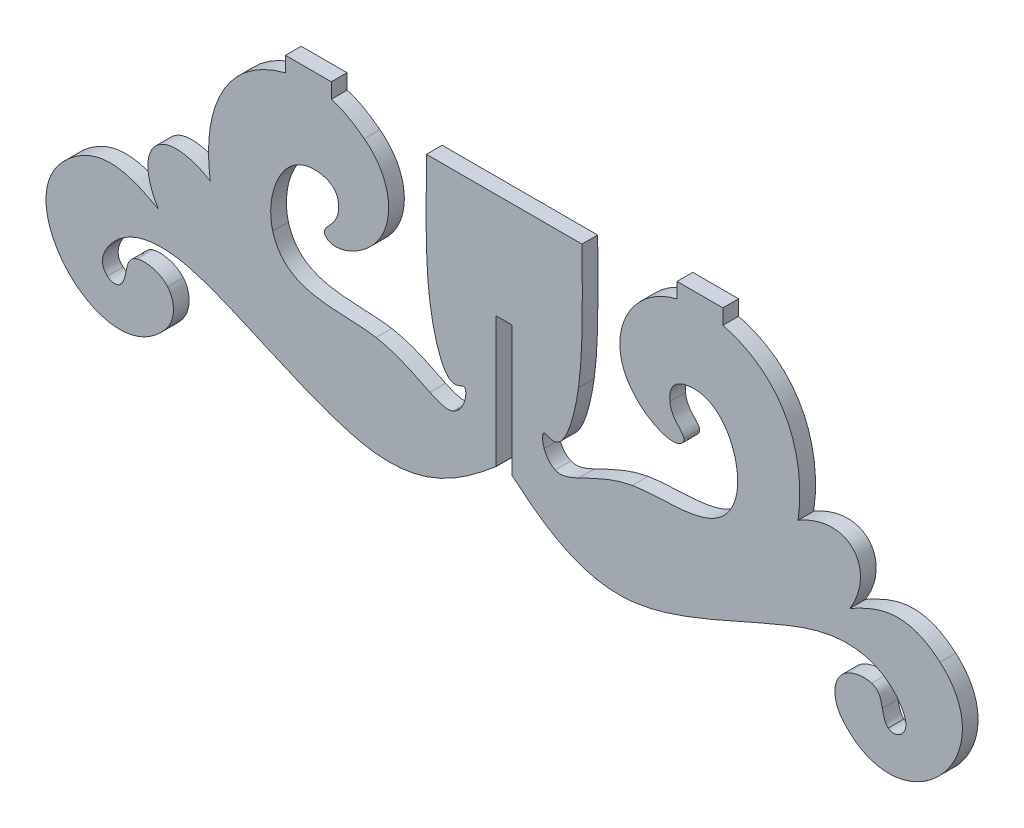
SolidWorks part; units mm, degrees
ref_plane "Plano frontal" through (0, 0, 0) normal (0, 0, 1) x (1, 0, 0)
ref_plane "Plano superior" through (0, 0, 0) normal (0, 1, 0) x (1, 0, 0)
ref_plane "Plano direito" through (0, 0, 0) normal (1, 0, 0) x (0, 0, -1)
sketch "Model" plane through (0, 0, 0) normal (0, 0, 1) x (1, 0, 0)
  line L0 (4.7123, 71.0422) -> (4.7123, 54.4506)
  line L1 (4.7123, 54.4506) -> (4.6872, 54.4506)
  line L2 (31.5377, 84.4254) -> (31.5377, 86.3583)
  line L3 (31.5377, 86.3583) -> (25.7044, 86.3583)
  line L4 (25.7044, 86.3583) -> (25.7044, 84.4254)
  line L5 (13.5969, 84.4174) -> (9.529, 84.4174)
  line L6 (9.529, 84.4174) -> (9.529, 86.3542)
  line L7 (9.529, 86.3542) -> (-2.1377, 86.3542)
  line L8 (-2.1377, 86.3542) -> (-2.1377, 84.4174)
  line L9 (-2.1377, 84.4174) -> (-6.2057, 84.4174)
  line L10 (-18.3132, 84.4254) -> (-18.3132, 86.3598)
  line L11 (-18.3132, 86.3598) -> (-24.1465, 86.3598)
  line L12 (-24.1465, 86.3598) -> (-24.1465, 84.4254)
  line L13 (2.704, 54.4506) -> (2.6789, 54.4506)
  line L14 (2.6789, 54.4506) -> (2.6789, 71.0422)
  line L15 (2.6789, 71.0422) -> (4.7123, 71.0422)
  line L16 (-56.1236, 45.5782) -> (63.2543, 45.5782) construction
  line L58 (-2.1377, 84.4174) -> (9.529, 84.4174)
  spline S0 degree 3 poles (4.6872, 54.4506) (9.062, 50.7507) (13.7394, 47.386) (20.3781, 48.2488) knots 0.027778 0.027778 0.027778 0.027778 0.041667 0.041667 0.041667 0.041667
  spline S1 degree 3 poles (20.3781, 48.2488) (27.5885, 49.1858) (37.2734, 55.11) (43.5948, 56.7666) knots 0.041667 0.041667 0.041667 0.041667 0.055556 0.055556 0.055556 0.055556
  spline S2 degree 3 poles (43.5948, 56.7666) (49.9162, 58.4234) (52.8741, 55.8127) (54.0948, 54.0027) knots 0.055556 0.055556 0.055556 0.055556 0.069444 0.069444 0.069444 0.069444
  spline S3 degree 3 poles (54.0948, 54.0027) (55.3154, 52.1926) (54.7989, 51.1833) (54.2189, 50.6878) knots 0.069444 0.069444 0.069444 0.069444 0.083333 0.083333 0.083333 0.083333
  spline S4 degree 3 poles (54.2189, 50.6878) (53.6389, 50.1923) (52.9955, 50.2106) (52.5865, 50.5521) knots 0.083333 0.083333 0.083333 0.083333 0.097222 0.097222 0.097222 0.097222
  spline S5 degree 3 poles (52.5865, 50.5521) (52.1774, 50.8936) (52.0028, 51.5583) (51.8381, 52.3634) knots 0.097222 0.097222 0.097222 0.097222 0.111111 0.111111 0.111111 0.111111
  spline S6 degree 3 poles (51.8381, 52.3634) (51.6733, 53.1686) (51.5184, 54.1141) (50.4808, 54.4478) knots 0.111111 0.111111 0.111111 0.111111 0.125 0.125 0.125 0.125
  spline S7 degree 3 poles (50.4808, 54.4478) (49.4432, 54.7814) (47.5229, 54.5032) (46.5324, 53.3213) knots 0.125 0.125 0.125 0.125 0.138889 0.138889 0.138889 0.138889
  spline S8 degree 3 poles (46.5324, 53.3213) (45.5419, 52.1394) (45.4813, 50.0538) (46.8609, 48.4462) knots 0.138889 0.138889 0.138889 0.138889 0.152778 0.152778 0.152778 0.152778
  spline S9 degree 3 poles (46.8609, 48.4462) (54.5024, 39.5417) (67.8873, 53.5286) (59.1979, 61.1094) knots 0.152778 0.152778 0.152778 0.152778 0.166667 0.166667 0.166667 0.166667
  spline S10 degree 3 poles (59.1979, 61.1094) (54.8331, 64.9174) (51.0322, 63.0994) (47.7303, 61.3186) knots 0.166667 0.166667 0.166667 0.166667 0.180556 0.180556 0.180556 0.180556
  spline S11 degree 3 poles (47.7303, 61.3186) (51.1536, 66.909) (47.6105, 71.4976) (41.1094, 67.7169) knots 0.180556 0.180556 0.180556 0.180556 0.194444 0.194444 0.194444 0.194444
  spline S12 degree 3 poles (41.1094, 67.7169) (42.1976, 75.1571) (39.464, 82.3954) (31.5377, 84.4254) knots 0.194444 0.194444 0.194444 0.194444 0.208333 0.208333 0.208333 0.208333
  spline S13 degree 3 poles (25.7044, 84.4254) (18.8302, 82.7817) (15.2664, 74.1022) (22.078, 69.5651) knots 0.25 0.25 0.25 0.25 0.263889 0.263889 0.263889 0.263889
  spline S14 degree 3 poles (22.078, 69.5651) (23.2846, 68.7615) (24.5438, 68.3933) (25.3837, 68.4581) knots 0.263889 0.263889 0.263889 0.263889 0.277778 0.277778 0.277778 0.277778
  spline S15 degree 3 poles (25.3837, 68.4581) (26.2235, 68.523) (26.6439, 69.0208) (26.5749, 69.4768) knots 0.277778 0.277778 0.277778 0.277778 0.291667 0.291667 0.291667 0.291667
  spline S16 degree 3 poles (26.5749, 69.4768) (26.4546, 70.2717) (24.9711, 70.8288) (24.7886, 72.6586) knots 0.291667 0.291667 0.291667 0.291667 0.305556 0.305556 0.305556 0.305556
  spline S17 degree 3 poles (24.7886, 72.6586) (24.5774, 74.7766) (26.0542, 75.6463) (28.0005, 75.5977) knots 0.305556 0.305556 0.305556 0.305556 0.319444 0.319444 0.319444 0.319444
  spline S18 degree 3 poles (28.0005, 75.5977) (32.2189, 75.4923) (34.1657, 69.6758) (33.1666, 66.1718) knots 0.319444 0.319444 0.319444 0.319444 0.333333 0.333333 0.333333 0.333333
  spline S19 degree 3 poles (33.1666, 66.1718) (31.4794, 60.2548) (24.54, 61.8192) (19.997, 61.0131) knots 0.333333 0.333333 0.333333 0.333333 0.347222 0.347222 0.347222 0.347222
  spline S20 degree 3 poles (19.997, 61.0131) (17.1907, 60.5153) (14.7474, 59.143) (13.1565, 58.3983) knots 0.347222 0.347222 0.347222 0.347222 0.361111 0.361111 0.361111 0.361111
  spline S21 degree 3 poles (13.1565, 58.3983) (11.5657, 57.6536) (10.8273, 57.5364) (10.1985, 57.8083) knots 0.361111 0.361111 0.361111 0.361111 0.375 0.375 0.375 0.375
  spline S22 degree 3 poles (10.1985, 57.8083) (9.5697, 58.0801) (9.0504, 58.7408) (8.7848, 59.4751) knots 0.375 0.375 0.375 0.375 0.388889 0.388889 0.388889 0.388889
  spline S23 degree 3 poles (8.7848, 59.4751) (8.5191, 60.2093) (8.507, 61.0171) (8.775, 61.1741) knots 0.388889 0.388889 0.388889 0.388889 0.402778 0.402778 0.402778 0.402778
  spline S24 degree 3 poles (8.775, 61.1741) (9.043, 61.3311) (9.8672, 60.4358) (10.7531, 61.1993) knots 0.402778 0.402778 0.402778 0.402778 0.416667 0.416667 0.416667 0.416667
  spline S25 degree 3 poles (10.7531, 61.1993) (11.639, 61.9629) (12.5865, 64.3852) (13.1576, 68.364) knots 0.416667 0.416667 0.416667 0.416667 0.430556 0.430556 0.430556 0.430556
  spline S26 degree 3 poles (13.1576, 68.364) (13.7287, 72.3427) (13.6784, 78.4807) (13.5969, 84.4174) knots 0.430556 0.430556 0.430556 0.430556 0.444444 0.444444 0.444444 0.444444
  spline S27 degree 3 poles (-6.2057, 84.4174) (-6.2872, 78.4807) (-6.3375, 72.3427) (-5.7664, 68.364) knots 0.513889 0.513889 0.513889 0.513889 0.527778 0.527778 0.527778 0.527778
  spline S28 degree 3 poles (-5.7664, 68.364) (-5.1953, 64.3852) (-4.2478, 61.9629) (-3.3619, 61.1993) knots 0.527778 0.527778 0.527778 0.527778 0.541667 0.541667 0.541667 0.541667
  spline S29 degree 3 poles (-3.3619, 61.1993) (-2.476, 60.4358) (-1.6518, 61.3311) (-1.3838, 61.1741) knots 0.541667 0.541667 0.541667 0.541667 0.555556 0.555556 0.555556 0.555556
  spline S30 degree 3 poles (-1.3838, 61.1741) (-1.1158, 61.0171) (-1.1279, 60.2093) (-1.3936, 59.4751) knots 0.555556 0.555556 0.555556 0.555556 0.569444 0.569444 0.569444 0.569444
  spline S31 degree 3 poles (-1.3936, 59.4751) (-1.6592, 58.7408) (-2.1785, 58.0801) (-2.8073, 57.8083) knots 0.569444 0.569444 0.569444 0.569444 0.583333 0.583333 0.583333 0.583333
  spline S32 degree 3 poles (-2.8073, 57.8083) (-3.4361, 57.5364) (-4.1745, 57.6536) (-5.7653, 58.3983) knots 0.583333 0.583333 0.583333 0.583333 0.597222 0.597222 0.597222 0.597222
  spline S33 degree 3 poles (-5.7653, 58.3983) (-7.3562, 59.143) (-9.7995, 60.5153) (-12.6058, 61.0131) knots 0.597222 0.597222 0.597222 0.597222 0.611111 0.611111 0.611111 0.611111
  spline S34 degree 3 poles (-12.6058, 61.0131) (-17.1488, 61.8192) (-24.0882, 60.2548) (-25.7754, 66.1718) knots 0.611111 0.611111 0.611111 0.611111 0.625 0.625 0.625 0.625
  spline S35 degree 3 poles (-25.7754, 66.1718) (-26.7745, 69.6758) (-24.8277, 75.4923) (-20.6093, 75.5977) knots 0.625 0.625 0.625 0.625 0.638889 0.638889 0.638889 0.638889
  spline S36 degree 3 poles (-20.6093, 75.5977) (-18.663, 75.6463) (-17.1862, 74.7766) (-17.3974, 72.6586) knots 0.638889 0.638889 0.638889 0.638889 0.652778 0.652778 0.652778 0.652778
  spline S37 degree 3 poles (-17.3974, 72.6586) (-17.5799, 70.8288) (-19.0634, 70.2717) (-19.1837, 69.4768) knots 0.652778 0.652778 0.652778 0.652778 0.666667 0.666667 0.666667 0.666667
  spline S38 degree 3 poles (-19.1837, 69.4768) (-19.2527, 69.0208) (-18.8323, 68.523) (-17.9925, 68.4581) knots 0.666667 0.666667 0.666667 0.666667 0.680556 0.680556 0.680556 0.680556
  spline S39 degree 3 poles (-17.9925, 68.4581) (-17.1526, 68.3933) (-15.8934, 68.7615) (-14.6868, 69.5651) knots 0.680556 0.680556 0.680556 0.680556 0.694444 0.694444 0.694444 0.694444
  spline S40 degree 3 poles (-14.6868, 69.5651) (-10.0229, 72.6717) (-9.7672, 78.8737) (-14.1156, 82.1811) knots 0.694444 0.694444 0.694444 0.694444 0.708333 0.708333 0.708333 0.708333
  spline S41 degree 3 poles (-14.1156, 82.1811) (-15.2489, 83.0431) (-16.7518, 84.052) (-18.3132, 84.4254) knots 0.708333 0.708333 0.708333 0.708333 0.722222 0.722222 0.722222 0.722222
  spline S42 degree 3 poles (-24.1465, 84.4254) (-32.0728, 82.3954) (-34.8065, 75.1571) (-33.7182, 67.7169) knots 0.763889 0.763889 0.763889 0.763889 0.777778 0.777778 0.777778 0.777778
  spline S43 degree 3 poles (-33.7182, 67.7169) (-40.2193, 71.4976) (-43.7624, 66.909) (-40.3391, 61.3186) knots 0.777778 0.777778 0.777778 0.777778 0.791667 0.791667 0.791667 0.791667
  spline S44 degree 3 poles (-40.3391, 61.3186) (-43.641, 63.0994) (-47.4419, 64.9174) (-51.8067, 61.1094) knots 0.791667 0.791667 0.791667 0.791667 0.805556 0.805556 0.805556 0.805556
  spline S45 degree 3 poles (-51.8067, 61.1094) (-60.4961, 53.5286) (-47.1112, 39.5417) (-39.4697, 48.4462) knots 0.805556 0.805556 0.805556 0.805556 0.819444 0.819444 0.819444 0.819444
  spline S46 degree 3 poles (-39.4697, 48.4462) (-38.0901, 50.0538) (-38.1507, 52.1394) (-39.1412, 53.3213) knots 0.819444 0.819444 0.819444 0.819444 0.833333 0.833333 0.833333 0.833333
  spline S47 degree 3 poles (-39.1412, 53.3213) (-40.1317, 54.5032) (-42.052, 54.7814) (-43.0896, 54.4478) knots 0.833333 0.833333 0.833333 0.833333 0.847222 0.847222 0.847222 0.847222
  spline S48 degree 3 poles (-43.0896, 54.4478) (-44.1272, 54.1141) (-44.2821, 53.1686) (-44.4469, 52.3634) knots 0.847222 0.847222 0.847222 0.847222 0.861111 0.861111 0.861111 0.861111
  spline S49 degree 3 poles (-44.4469, 52.3634) (-44.6116, 51.5583) (-44.7862, 50.8936) (-45.1953, 50.5521) knots 0.861111 0.861111 0.861111 0.861111 0.875 0.875 0.875 0.875
  spline S50 degree 3 poles (-45.1953, 50.5521) (-45.6043, 50.2106) (-46.2477, 50.1923) (-46.8277, 50.6878) knots 0.875 0.875 0.875 0.875 0.888889 0.888889 0.888889 0.888889
  spline S51 degree 3 poles (-46.8277, 50.6878) (-47.4077, 51.1833) (-47.9242, 52.1926) (-46.7036, 54.0027) knots 0.888889 0.888889 0.888889 0.888889 0.902778 0.902778 0.902778 0.902778
  spline S52 degree 3 poles (-46.7036, 54.0027) (-45.4829, 55.8127) (-42.525, 58.4234) (-36.2036, 56.7666) knots 0.902778 0.902778 0.902778 0.902778 0.916667 0.916667 0.916667 0.916667
  spline S53 degree 3 poles (-36.2036, 56.7666) (-29.8822, 55.11) (-20.1973, 49.1858) (-12.9869, 48.2488) knots 0.916667 0.916667 0.916667 0.916667 0.930556 0.930556 0.930556 0.930556
  spline S54 degree 3 poles (-12.9869, 48.2488) (-6.3481, 47.386) (-1.6708, 50.7507) (2.704, 54.4506) knots 0.930556 0.930556 0.930556 0.930556 0.944444 0.944444 0.944444 0.944444
extrude "Ressalto-extrusão3" add sketch "Model" along normal blind 2 contours S53 S54 L13 L14 L15 L0 L1 S0 S1 S2 S3 S4 S5 S6 S7 S8 S9 S10 S11 S12 L2 L3 L4 S13 S14 S15 S16 S17 S18 S19 S20 S21 S22 S23 S24 S25 S26 L5 L6 L7 L8 L9 S27 S28 S29 S30 S31 S32 S33 S34 S35
